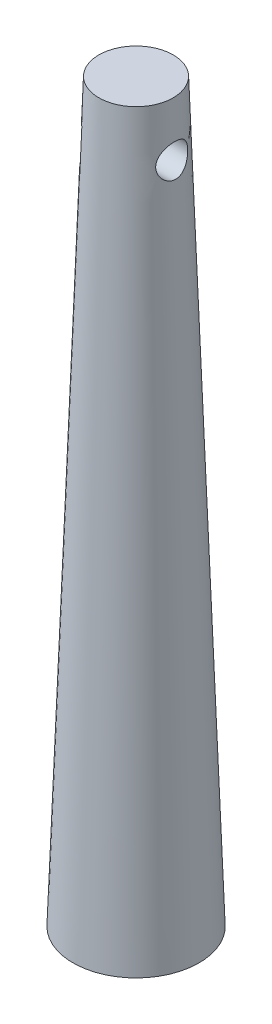
SolidWorks part; units mm, degrees
material "Plain Carbon Steel"
ref_plane "Front" through (0, 0, 0) normal (0, 0, 1) x (1, 0, 0)
ref_plane "Top" through (0, 0, 0) normal (0, 1, 0) x (1, 0, 0)
ref_plane "Right" through (0, 0, 0) normal (1, 0, 0) x (0, 0, -1)
sketch "Sketch1" plane through (0, 0, 0) normal (0, 0, 1) x (1, 0, 0)
  line L0 (0, 0) -> (0, 70.1548)
  line L1 (0, -50) -> (0, 50) construction
  line L2 (0, 70.1548) -> (3.5433, 70.1548)
  line L3 (3.5433, 70.1548) -> (6.0071, 0)
  line L4 (50, 0) -> (-50, 0) construction
  line L5 (6.0071, 0) -> (0, 0)
  dimension "D1" = 70.1548
  dimension "D2" = 6.0071
  dimension "D3" = 3.5433
revolve "Revolve1" add sketch "Sketch1" angle 360 about L0
sketch "Sketch2" plane through (0, 0, 0) normal (1, 0, 0) x (0, 0, -1)
  line L0 (0, 0) -> (0, 70.1548) construction
  line L1 (3.5433, 70.1548) -> (-3.5433, 70.1548) construction
  circle A0 centre (0, 65.0748) radius 1.524
  dimension "D1" = 5.08
  dimension "D2" = 3.048
extrude "Cut-Extrude1" cut sketch "Sketch2" against normal through all and the other way through all
